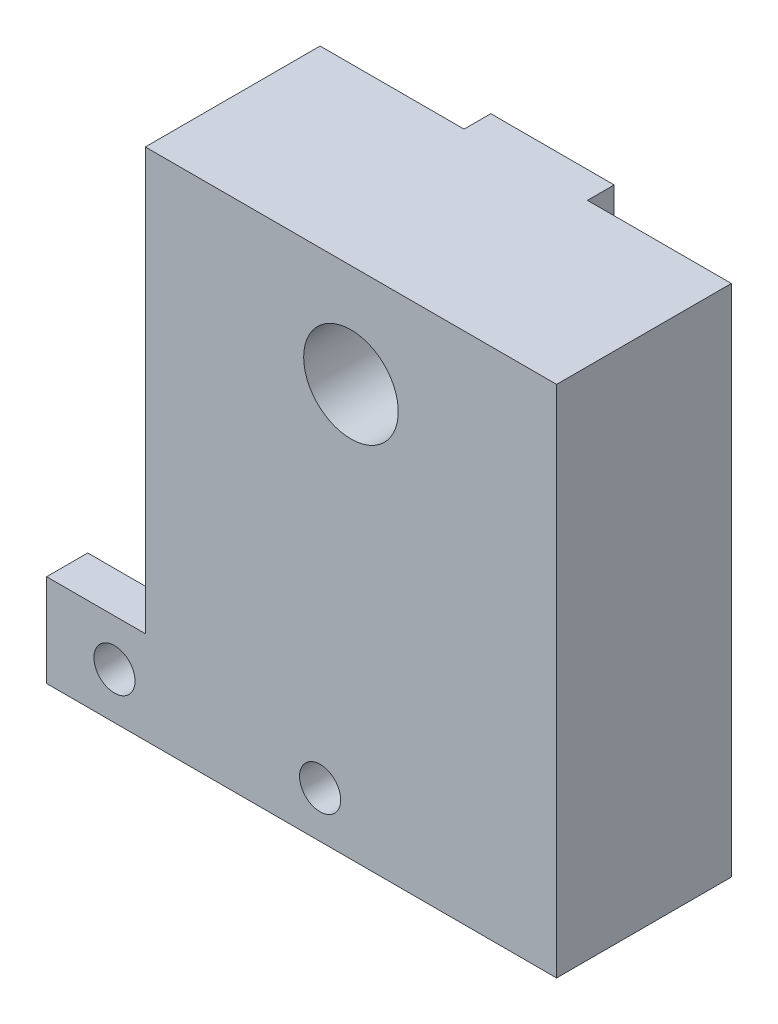
SolidWorks part; units mm, degrees
ref_plane "Front Plane" through (0, 0, 0) normal (0, 0, 1) x (1, 0, 0)
ref_plane "Top Plane" through (0, 0, 0) normal (0, 1, 0) x (1, 0, 0)
ref_plane "Right Plane" through (0, 0, 0) normal (1, 0, 0) x (0, 0, -1)
sketch "Sketch1" plane through (0, 0, 0) normal (0, 0, 1) x (1, 0, 0)
  line L1 (0, 0) -> (20, 0)
  line L2 (0, 0) -> (0, 25)
  line L3 (0, 25) -> (20, 25)
  line L4 (20, 0) -> (20, 25)
  dimension "D1" = 20
  dimension "D2" = 25
extrude "Boss-Extrude1" add sketch "Sketch1" along normal blind 2
sketch "Sketch4" plane through (0, 0, 0) normal (0, 0, -1) x (-1, 0, 0)
  line L1 (-20, 25) -> (0, 25)
  line L2 (-20, 25) -> (-20, 15)
  line L3 (-20, 15) -> (0, 15)
  line L4 (0, 25) -> (0, 15)
  line L5 (0, 25) -> (0, 0) construction
  dimension "D1" = 10
extrude "Boss-Extrude3" add sketch "Sketch4" along normal blind 6.5
sketch "Sketch9" plane through (0, 0, -6.5) normal (0, 0, -1) x (-1, 0, 0)
  line L0 (-10, 25) -> (-10, 15) construction
  line L1 (0, 25) -> (-20, 25) construction
  line L2 (-20, 15) -> (0, 15) construction
  line L4 (-13, 15) -> (-7, 15)
  line L5 (-13, 15) -> (-13, 25)
  line L6 (-13, 25) -> (-7, 25)
  line L7 (-7, 15) -> (-7, 25)
  line L8 (-13, 15) -> (-7, 25) construction
  line L9 (-13, 25) -> (-7, 15) construction
  point P6 (-10, 20)
  dimension "D1" = 6
extrude "Boss-Extrude6" add sketch "Sketch9" along normal blind 1.3
sketch "Sketch5" plane through (0, 0, -6.5) normal (0, 0, -1) x (-1, 0, 0)
  line L0 (-20, 20) -> (0, 20) construction
  line L1 (-20, 25) -> (-20, 15) construction
  line L2 (0, 15) -> (0, 25) construction
  circle A0 centre (-10, 20) radius 2.3
  dimension "D1" = 4.6
extrude "Cut-Extrude2" cut sketch "Sketch5" against normal through all both and the other way through all
sketch "Sketch6" plane through (0, 0, 2) normal (0, 0, 1) x (1, 0, 0)
  line L1 (0, 0) -> (-4.8, 0)
  line L2 (0, 0) -> (0, 4.5)
  line L3 (0, 4.5) -> (-4.8, 4.5)
  line L4 (-4.8, 0) -> (-4.8, 4.5)
  dimension "D1" = 4.8
  dimension "D2" = 4.5
extrude "Boss-Extrude4" add sketch "Sketch6" against normal up to surface (2 mm away) up to face at (10, 7.5, 0)
sketch "Sketch7" plane through (0, 0, 0) normal (0, 0, -1) x (-1, 0, 0)
  line L0 (4.8, 2.25) -> (-20, 2.25) construction
  line L1 (4.8, 4.5) -> (4.8, 0) construction
  line L2 (-20, 0) -> (-20, 15) construction
  circle A0 centre (1.5, 2.25) radius 1
  circle A1 centre (-8.5, 2.25) radius 1
  dimension "D2" = 2
  dimension "D3" = 2
  dimension "D1" = 10
  dimension "D4" = 11.5
extrude "Cut-Extrude3" cut sketch "Sketch7" against normal blind 10
sketch "Sketch8" plane through (0, 0, 0) normal (0, 0, -1) x (-1, 0, 0)
  line L0 (4.8, 0) -> (-20, 0) construction
  line L1 (-20, 15) -> (-18, 15)
  line L2 (-20, 15) -> (-20, 0)
  line L3 (-20, 0) -> (-18, 0)
  line L4 (-18, 15) -> (-18, 0)
  dimension "D1" = 2
extrude "Boss-Extrude5" add sketch "Sketch8" along normal up to surface (6.5 mm away) up to face at (3.5, 20, -6.5)
